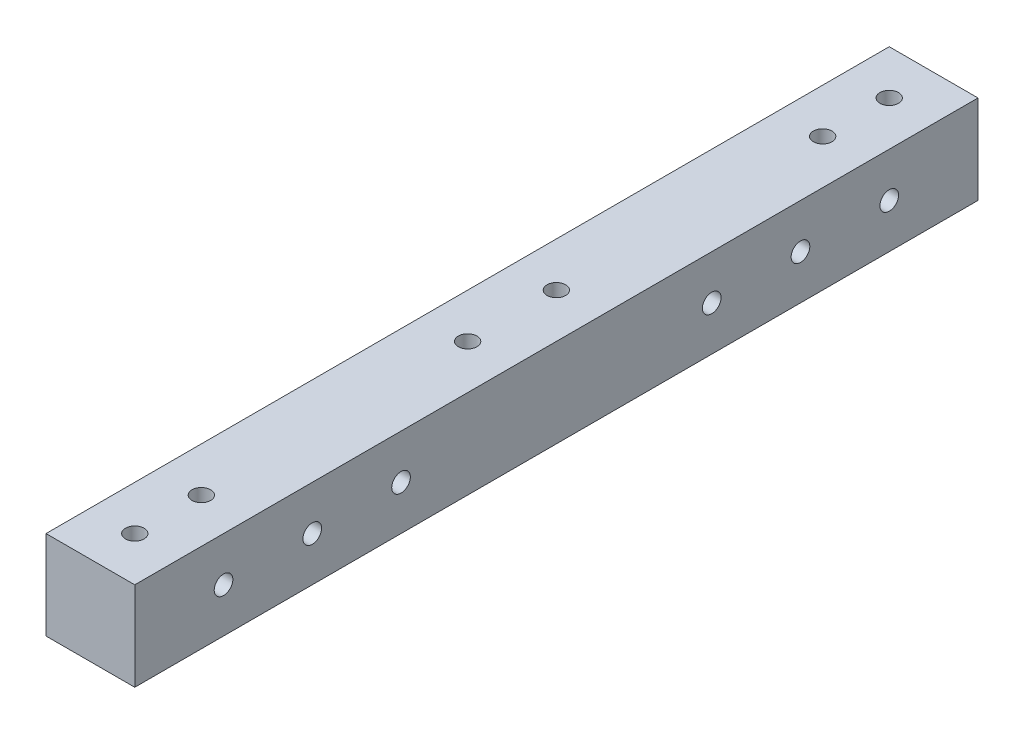
SolidWorks part; units mm, degrees
ref_plane "前视基准面" through (0, 0, 0) normal (0, 0, 1) x (1, 0, 0)
ref_plane "上视基准面" through (0, 0, 0) normal (0, 1, 0) x (1, 0, 0)
ref_plane "右视基准面" through (0, 0, 0) normal (1, 0, 0) x (0, 0, -1)
other "Configuration Table"
sketch "草图1" plane through (0, 0, 0) normal (0, 0, 1) x (1, 0, 0)
  line L1 (-10, 10) -> (10, 10)
  line L2 (-10, 10) -> (-10, -10)
  line L3 (-10, -10) -> (10, -10)
  line L4 (10, 10) -> (10, -10)
  line L5 (-10, 10) -> (10, -10) construction
  line L6 (-10, -10) -> (10, 10) construction
  point P0 (0, 0)
  dimension "D1" = 20
  dimension "D2" = 20
extrude "凸台-拉伸1" add sketch "草图1" along normal blind 190
sketch "草图2" plane through (-10, 0, 0) normal (-1, 0, 0) x (0, 0, 1)
  line L0 (-8.2357, 0) -> (199.8456, 0) construction
  line L1 (95, 10) -> (95, -36.1224) construction
  line L2 (190, 10) -> (0, 10) construction
  circle A1 centre (40, 0) radius 2.1
  circle A2 centre (20, 0) radius 2.1
  circle A3 centre (60, 0) radius 2.1
  circle A4 centre (130, 0) radius 2.1
  circle A5 centre (170, 0) radius 2.1
  circle A6 centre (150, 0) radius 2.1
  point P19 (0, 0)
  dimension "D1" = 55
  dimension "D2" = 4.2
  dimension "D3" = 20
  dimension "D4" = 20
  dimension "D5" = 4.2
  dimension "D6" = 4.2
extrude "切除-拉伸1" cut sketch "草图2" against normal blind 67
sketch "草图3" plane through (0, 10, 0) normal (0, 1, 0) x (1, 0, 0)
  line L0 (0, -190) -> (0, -116.2634) construction
  line L1 (10, -190) -> (-10, -190) construction
  line L3 (-10, -95) -> (124.6873, -95) construction
  line L4 (-10, -190) -> (-10, 0) construction
  line L5 (0, 0) -> (0, -73.7366) construction
  circle A0 centre (0, -180) radius 2.1
  circle A1 centre (0, -165) radius 2.1
  circle A3 centre (0, -25) radius 2.1
  circle A4 centre (0, -10) radius 2.1
  dimension "D1" = 4.2
  dimension "D2" = 4.2
  dimension "D3" = 10
  dimension "D4" = 15
extrude "切除-拉伸2" cut sketch "草图3" against normal blind 32
sketch "草图4" plane through (0, 10, 0) normal (0, 1, 0) x (1, 0, 0)
  line L0 (-10, -95) -> (10, -95) construction
  line L1 (-10, -190) -> (-10, 0) construction
  line L2 (10, -190) -> (10, 0) construction
  circle A0 centre (0, -85) radius 2.1
  circle A1 centre (0, -105) radius 2.1
  dimension "D1" = 4.2
  dimension "D2" = 10
  dimension "D3" = 10
extrude "切除-拉伸3" cut sketch "草图4" against normal through all
sketch "草图5" plane through (-10, 0, 0) normal (-1, 0, 0) x (0, 0, 1)
  line L0 (190, 10) -> (0, 10) construction
  circle A0 centre (95.9223, 0) radius 2.1
  point P3 (0, 0)
  dimension "D1" = 4.2
  dimension "D2" = 10
